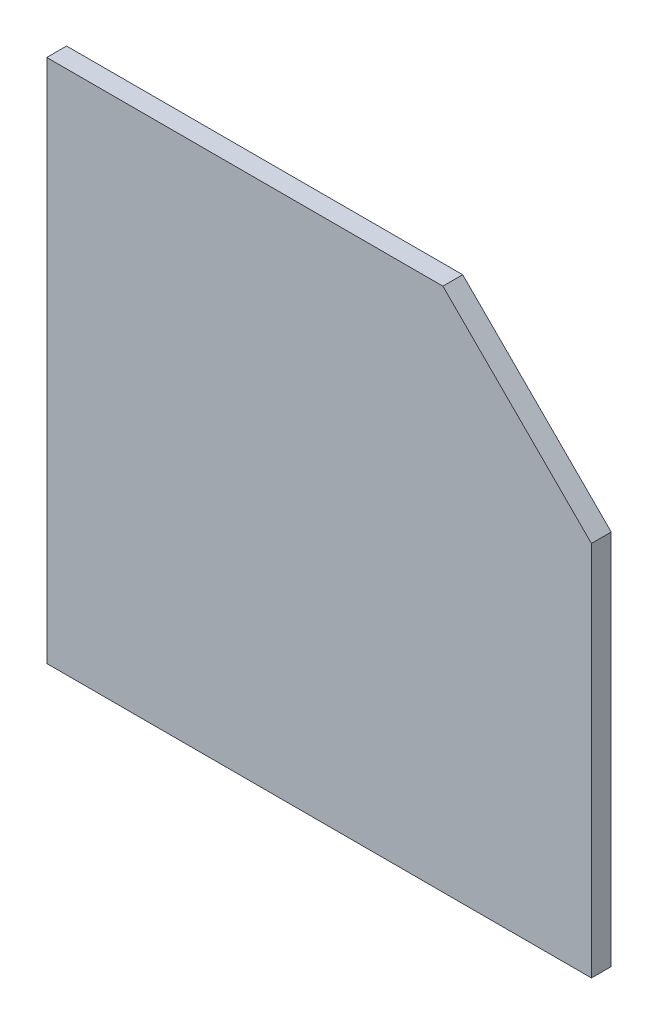
SolidWorks part; units mm, degrees
material "201 Annealed Stainless Steel (SS)"
ref_plane "Front Plane" through (0, 0, 0) normal (0, 0, 1) x (1, 0, 0)
ref_plane "Top Plane" through (0, 0, 0) normal (0, 1, 0) x (1, 0, 0)
ref_plane "Right Plane" through (0, 0, 0) normal (1, 0, 0) x (0, 0, -1)
sketch "Sketch1" plane through (0, 0, 0) normal (0, 0, 1) x (1, 0, 0)
  line L1 (0, 0) -> (-1100, 0)
  line L2 (0, 0) -> (0, 1060)
  line L3 (0, 1060) -> (-1100, 1060)
  line L4 (-1100, 0) -> (-1100, 1060)
  dimension "D1" = 1100
  dimension "D2" = 1060
extrude "Boss-Extrude1" add sketch "Sketch1" along normal blind 40
sketch "Sketch2" plane through (0, 0, 40) normal (0, 0, 1) x (1, 0, 0)
  line L0 (-300, 1060) -> (0, 760)
  line L1 (0, 1060) -> (-1100, 1060) construction
  line L2 (0, 0) -> (0, 1060) construction
  dimension "D1" = 300
  dimension "D2" = 300
extrude "Cut-Extrude1" cut sketch "Sketch2" against normal blind 40 and the other way through all
